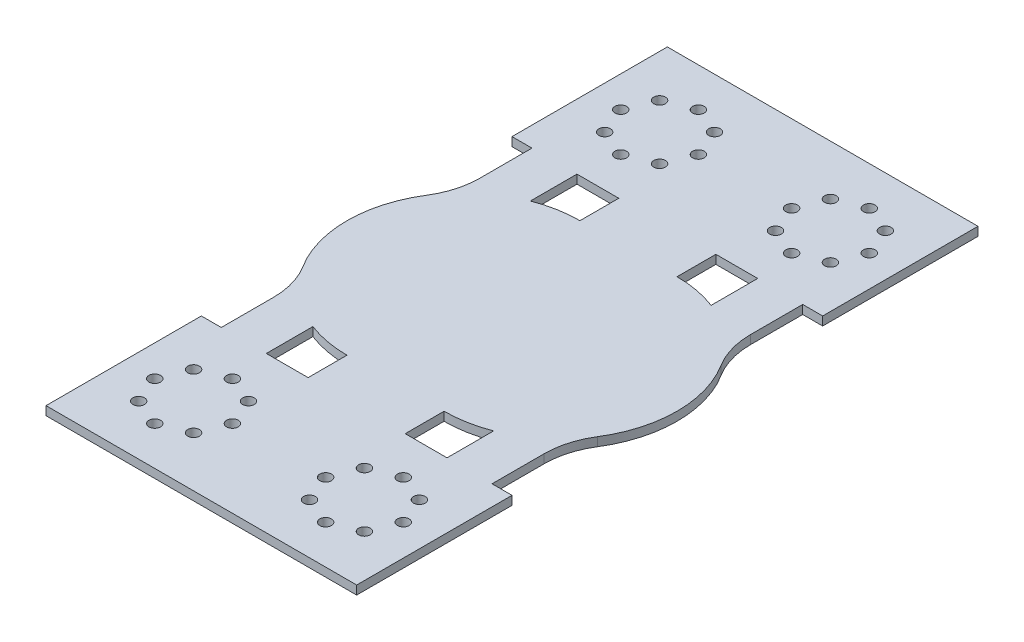
SolidWorks part; units mm, degrees
ref_plane "Alzado" through (0, 0, 0) normal (0, 0, 1) x (1, 0, 0)
ref_plane "Planta" through (0, 0, 0) normal (0, 1, 0) x (1, 0, 0)
ref_plane "Vista lateral" through (0, 0, 0) normal (1, 0, 0) x (0, 0, -1)
sketch "Croquis1" plane through (0, 0, 0) normal (0, 1, 0) x (1, 0, 0)
  line L0 (-40, -40) -> (40, -40)
  line L1 (40, -40) -> (40, 0)
  line L2 (40, 0) -> (12.5, 0)
  line L3 (12.5, 0) -> (12.5, 80)
  line L4 (12.5, 80) -> (40, 80)
  line L5 (40, 80) -> (40, 120)
  line L6 (40, 120) -> (-40, 120)
  line L7 (-40, 120) -> (-40, 80)
  line L8 (-40, 80) -> (-12.5, 80)
  line L9 (-12.5, 80) -> (-12.5, 0)
  line L10 (-12.5, 0) -> (-40, 0)
  line L11 (-40, 0) -> (-40, -40)
  line L12 (12.5, 0) -> (-12.5, 0) construction
  line L13 (0, -40) -> (0, 120) construction
  line L15 (-12.5, 0) -> (-12.5, 40)
  line L16 (-34.8607, 80) -> (-34.8607, 60)
  line L18 (-23.2703, 80) -> (-23.2703, 68)
  line L19 (34.8607, 80) -> (34.8607, 60)
  line L20 (23.2703, 80) -> (23.2703, 68)
  line L21 (-12.5, 40) -> (12.5, 40) construction
  line L22 (34.8607, 0) -> (34.8607, 20)
  line L23 (23.2703, 0) -> (23.2703, 12)
  line L24 (-23.2703, 0) -> (-23.2703, 12)
  line L25 (-34.8607, 0) -> (-34.8607, 20)
  arc A2 (12.5, 70) -> (12.5, 10) centre (12.5, 40) cw
  arc A3 (-12.5, 70) -> (-12.5, 10) centre (-12.5, 40) ccw
  point P12 (0, -40)
  point P13 (0, 120)
  point P15 (0, 0)
  point P23 (-12.5, 40)
  dimension "D6" = 20
  dimension "D5" = 30
  dimension "D1" = 40
  dimension "D2" = 80
  dimension "D3" = 80
  dimension "D4" = 25
  dimension "D7" = 12
  dimension "D8" = 160
extrude "Saliente-Extruir1" add sketch "Croquis1" along normal blind 2.25 contours A2 L3 | L10 L11 L0 L1 L2 L3 L4 L5 L6 L7 L8 L9 L15 | L9 A3 | L22 A2 L23 L2 | L20 A2 L19 L4 | A3 L18 L8 L16 | A3 L25 L10 L24
sketch "Croquis2" plane through (0, 2.25, 0) normal (0, 1, 0) x (1, 0, 0)
  line L0 (40, -20) -> (-40, -20) construction
  line L1 (40, -40) -> (40, 0) construction
  line L2 (-40, 0) -> (-40, -40) construction
  line L3 (0, 120) -> (0, -40) construction
  line L4 (40, 120) -> (-40, 120) construction
  line L5 (-40, -40) -> (40, -40) construction
  line L6 (-42.5, 40) -> (42.5, 40) construction
  circle A0 centre (32, -20) radius 1.5
  circle A1 centre (29.0711, -27.0711) radius 1.5
  circle A2 centre (22, -30) radius 1.5
  circle A3 centre (14.9289, -27.0711) radius 1.5
  circle A4 centre (12, -20) radius 1.5
  circle A5 centre (14.9289, -12.9289) radius 1.5
  circle A6 centre (22, -10) radius 1.5
  circle A7 centre (29.0711, -12.9289) radius 1.5
  arc A8 (-34.8607, 60) -> (-34.8607, 20) centre (-12.5, 40) ccw construction
  arc A9 (34.8607, 20) -> (34.8607, 60) centre (12.5, 40) ccw construction
  circle A10 centre (-29.0711, -12.9289) radius 1.5
  circle A11 centre (-22, -10) radius 1.5
  circle A12 centre (-14.9289, -12.9289) radius 1.5
  circle A13 centre (-12, -20) radius 1.5
  circle A14 centre (-14.9289, -27.0711) radius 1.5
  circle A15 centre (-22, -30) radius 1.5
  circle A16 centre (-29.0711, -27.0711) radius 1.5
  circle A17 centre (-32, -20) radius 1.5
  circle A18 centre (-32, 100) radius 1.5
  circle A19 centre (-29.0711, 107.0711) radius 1.5
  circle A20 centre (-22, 110) radius 1.5
  circle A21 centre (-14.9289, 107.0711) radius 1.5
  circle A22 centre (-12, 100) radius 1.5
  circle A23 centre (-14.9289, 92.9289) radius 1.5
  circle A24 centre (-22, 90) radius 1.5
  circle A25 centre (-29.0711, 92.9289) radius 1.5
  circle A26 centre (29.0711, 92.9289) radius 1.5
  circle A27 centre (22, 90) radius 1.5
  circle A28 centre (14.9289, 92.9289) radius 1.5
  circle A29 centre (12, 100) radius 1.5
  circle A30 centre (14.9289, 107.0711) radius 1.5
  circle A31 centre (22, 110) radius 1.5
  circle A32 centre (29.0711, 107.0711) radius 1.5
  circle A33 centre (32, 100) radius 1.5
  point P8 (22, -20)
  point P25 (22, -20)
  point P54 (-22, -20)
  point P87 (-22, 100)
  point P88 (22, 100)
  dimension "D1" = 3
  dimension "D2" = 8
  dimension "D3" = 10
  dimension "D4" = 8
extrude "Cortar-Extruir1" cut sketch "Croquis2" against normal through all
fillet "Redondeo1" radius 20 4 edges at (-34.8607, 1.125, -60) (-34.8607, 1.125, -20) (34.8607, 1.125, -20) (34.8607, 1.125, -60)
